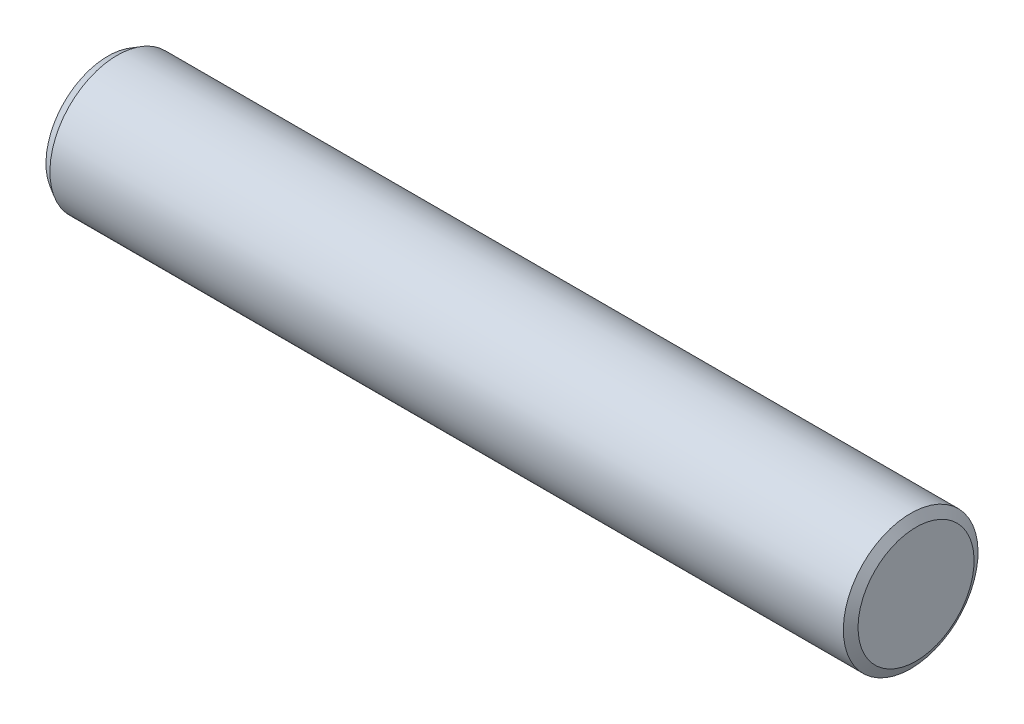
SolidWorks part; units mm, degrees
material "1060-H12 Rod (SS)"
ref_plane "Front Plane" through (0, 0, 0) normal (0, 0, 1) x (1, 0, 0)
ref_plane "Top Plane" through (0, 0, 0) normal (0, 1, 0) x (1, 0, 0)
ref_plane "Right Plane" through (0, 0, 0) normal (1, 0, 0) x (0, 0, -1)
sketch "Sketch1" plane through (0, 0, 0) normal (0, 0, 1) x (1, 0, 0)
  line L1 (0, 0) -> (-30, 0)
  line L2 (0, 0) -> (0, 2.5)
  line L3 (0, 2.5) -> (-30, 2.5)
  line L4 (-30, 0) -> (-30, 2.5)
  dimension "D1" = 2.5
  dimension "D2" = 30
revolve "Revolve1" add sketch "Sketch1" angle 360 about L1
chamfer "Chamfer1" distance 0.2 angle 60 2 edges at (-30, 2.5, 0) (0, 2.5, 0)
ref_plane "Plane1" through (-15, 0, 0) normal (1, 0, 0) x (0, 0, -1)
